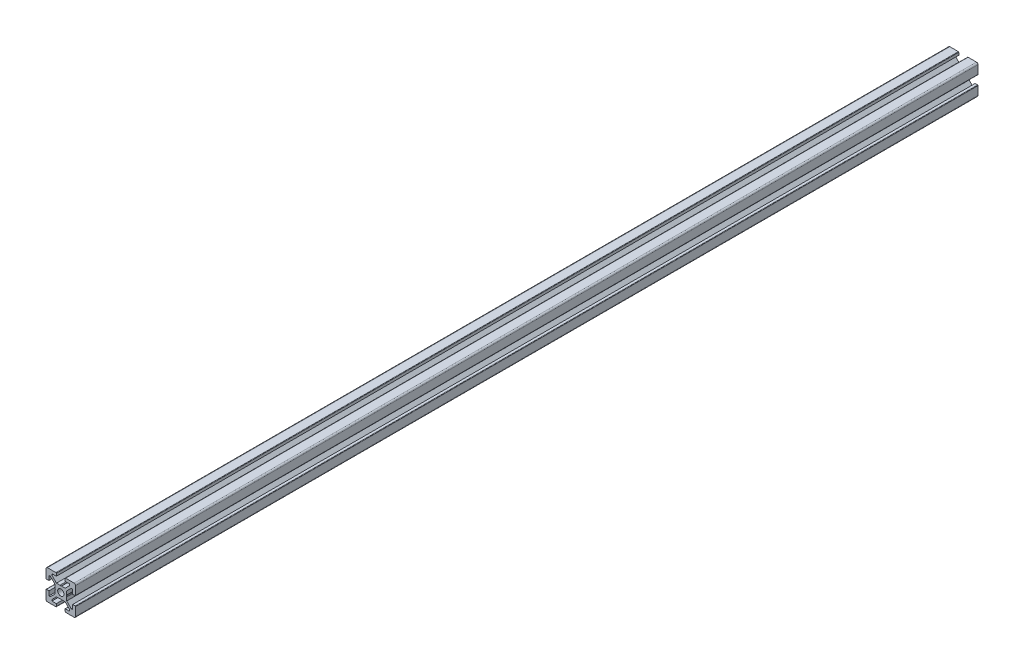
SolidWorks part; units mm, degrees
ref_plane "Front Plane" through (0, 0, 0) normal (0, 0, 1) x (1, 0, 0)
ref_plane "Top Plane" through (0, 0, 0) normal (0, 1, 0) x (1, 0, 0)
ref_plane "Right Plane" through (0, 0, 0) normal (1, 0, 0) x (0, 0, -1)
ref_plane "Plane1" through (0, 0, 0) normal (0, 0, 1) x (1, 0, 0)
sketch "Sketch1" plane through (0, 0, 0) normal (0, 0, 1) x (1, 0, 0)
  line L0 (-10, 9) -> (-10, 3.3)
  line L1 (-9.7, 3) -> (-8, 3)
  line L2 (-8, 3) -> (-8, 6)
  line L3 (-8, 6) -> (-7.0607, 6)
  line L4 (-7.0607, 6) -> (-4, 2.9393)
  line L5 (-4, 2.9393) -> (-4, 0.5196)
  line L6 (-4, 0.5196) -> (-3.7, 0)
  line L7 (-3.7, 0) -> (-4, -0.5196)
  line L8 (-4, -0.5196) -> (-4, -2.9393)
  line L9 (-4, -2.9393) -> (-7.0607, -6)
  line L10 (-7.0607, -6) -> (-8, -6)
  line L11 (-8, -6) -> (-8, -3)
  line L12 (-8, -3) -> (-9.7, -3)
  line L13 (-10, -3.3) -> (-10, -9)
  line L14 (-9, -10) -> (-3.3, -10)
  line L15 (-3, -9.7) -> (-3, -8)
  line L16 (-3, -8) -> (-6, -8)
  line L17 (-6, -8) -> (-6, -7.0607)
  line L18 (-6, -7.0607) -> (-2.9393, -4)
  line L19 (-2.9393, -4) -> (-0.5196, -4)
  line L20 (-0.5196, -4) -> (0, -3.7)
  line L21 (0, -3.7) -> (0.5196, -4)
  line L22 (0.5196, -4) -> (2.9393, -4)
  line L23 (2.9393, -4) -> (6, -7.0607)
  line L24 (6, -7.0607) -> (6, -8)
  line L25 (6, -8) -> (3, -8)
  line L26 (3, -8) -> (3, -9.7)
  line L27 (3.3, -10) -> (9, -10)
  line L28 (10, -9) -> (10, -3.3)
  line L29 (9.7, -3) -> (8, -3)
  line L30 (8, -3) -> (8, -6)
  line L31 (8, -6) -> (7.0606, -6)
  line L32 (7.0606, -6) -> (4, -2.9393)
  line L33 (4, -2.9393) -> (4, -0.5196)
  line L34 (4, -0.5196) -> (3.7, 0)
  line L35 (3.7, 0) -> (4, 0.5196)
  line L36 (4, 0.5196) -> (4, 2.9393)
  line L37 (4, 2.9393) -> (7.0607, 6)
  line L38 (7.0607, 6) -> (8, 6)
  line L39 (8, 6) -> (8, 3)
  line L40 (8, 3) -> (9.7, 3)
  line L41 (10, 3.3) -> (10, 9)
  line L42 (9, 10) -> (3.3, 10)
  line L43 (3, 9.7) -> (3, 8)
  line L44 (3, 8) -> (6, 8)
  line L45 (6, 8) -> (6, 7.0607)
  line L46 (6, 7.0607) -> (2.9393, 4)
  line L47 (2.9393, 4) -> (0.5196, 4)
  line L48 (0.5196, 4) -> (0, 3.7)
  line L49 (0, 3.7) -> (-0.5196, 4)
  line L50 (-0.5196, 4) -> (-2.9394, 4)
  line L51 (-2.9394, 4) -> (-6, 7.0606)
  line L52 (-6, 7.0606) -> (-6, 8)
  line L53 (-6, 8) -> (-3, 8)
  line L54 (-3, 8) -> (-3, 9.7)
  line L55 (-3.3, 10) -> (-9, 10)
  arc A0 (-10, 3.3) -> (-9.7, 3) centre (-9.7, 3.3) ccw
  arc A1 (-9.7, -3) -> (-10, -3.3) centre (-9.7, -3.3) ccw
  arc A2 (-10, -9) -> (-9, -10) centre (-9, -9) ccw
  arc A3 (-3.3, -10) -> (-3, -9.7) centre (-3.3, -9.7) ccw
  arc A4 (3, -9.7) -> (3.3, -10) centre (3.3, -9.7) ccw
  arc A5 (9, -10) -> (10, -9) centre (9, -9) ccw
  arc A6 (10, -3.3) -> (9.7, -3) centre (9.7, -3.3) ccw
  arc A7 (9.7, 3) -> (10, 3.3) centre (9.7, 3.3) ccw
  arc A8 (10, 9) -> (9, 10) centre (9, 9) ccw
  arc A9 (3.3, 10) -> (3, 9.7) centre (3.3, 9.7) ccw
  arc A10 (-3, 9.7) -> (-3.3, 10) centre (-3.3, 9.7) ccw
  arc A11 (-9, 10) -> (-10, 9) centre (-9, 9) ccw
extrude "Boss-Extrude1" add sketch "Sketch1" against normal blind 609.5
ref_plane "Plane2" through (0, 0, 0) normal (1, 0, 0) x (0, 0, -1)
sketch "Sketch2" plane through (0, 0, 0) normal (1, 0, 0) x (0, 0, -1)
  line L0 (0, 0) -> (0, 2.1)
  line L1 (0, 2.1) -> (609.5, 2.1)
  line L2 (609.5, 2.1) -> (609.5, 0)
  line L3 (609.5, 0) -> (0, 0)
  line L4 (609.5, 0) -> (0, 0) construction
revolve "Cut-Revolve1" cut sketch "Sketch2" angle 360 about L4
